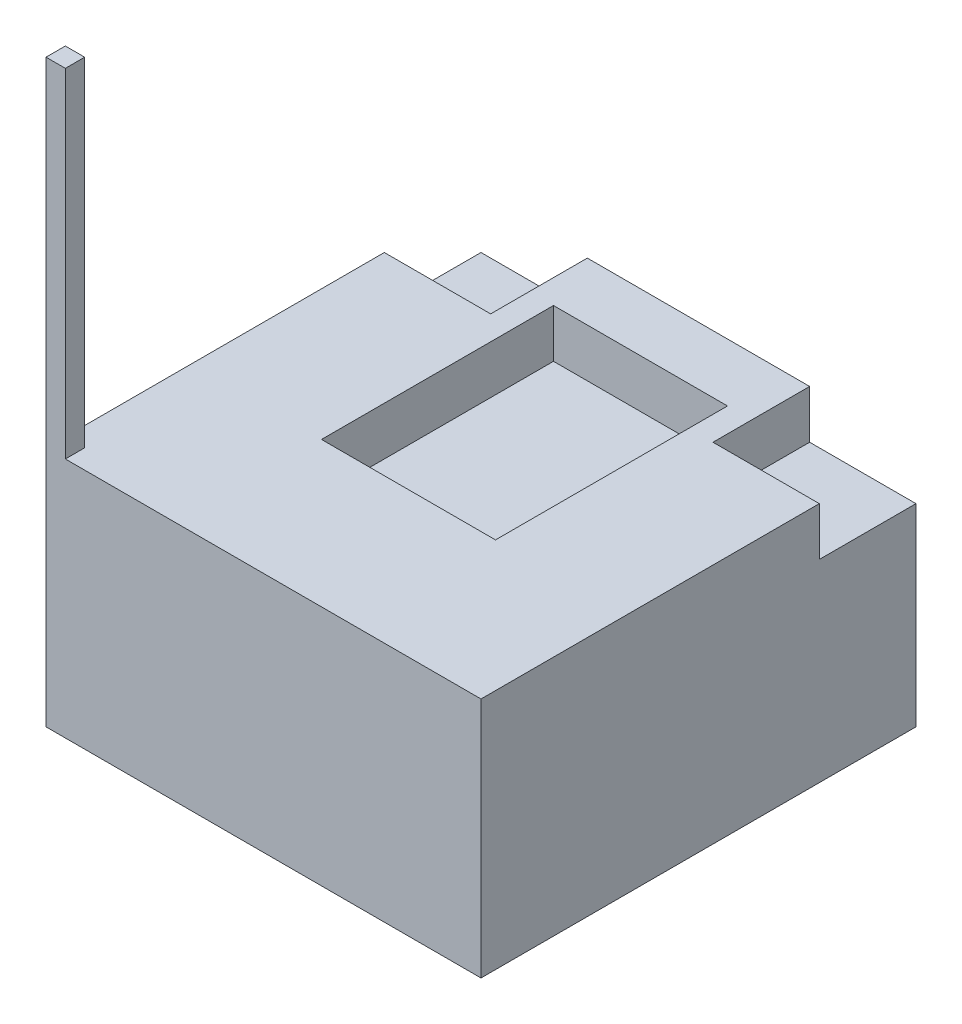
SolidWorks part; units mm, degrees
ref_plane "前视基准面" through (0, 0, 0) normal (0, 0, 1) x (1, 0, 0)
ref_plane "上视基准面" through (0, 0, 0) normal (0, 1, 0) x (1, 0, 0)
ref_plane "右视基准面" through (0, 0, 0) normal (1, 0, 0) x (0, 0, -1)
sketch "草图1" plane through (0, 0, 0) normal (0, 1, 0) x (1, 0, 0)
  line L1 (-225, 225) -> (225, 225)
  line L2 (-225, 225) -> (-225, -225)
  line L3 (-225, -225) -> (225, -225)
  line L4 (225, 225) -> (225, -225)
  line L5 (-225, 225) -> (225, -225) construction
  line L6 (-225, -225) -> (225, 225) construction
  point P0 (0, 0)
  dimension "D1" = 450
  dimension "D2" = 450
extrude "凸台-拉伸1" add sketch "草图1" along normal blind 250
sketch "草图2" plane through (0, 250, 0) normal (0, 1, 0) x (1, 0, 0)
  line L0 (0, 225) -> (0, 45) construction
  line L1 (-90, 165) -> (90, 165)
  line L2 (-90, 165) -> (-90, -75)
  line L3 (-90, -75) -> (90, -75)
  line L4 (90, 165) -> (90, -75)
  line L5 (-90, 165) -> (90, -75) construction
  line L6 (-90, -75) -> (90, 165) construction
  line L7 (225, 225) -> (-225, 225) construction
  point P0 (0, 45)
  dimension "D1" = 240
  dimension "D2" = 180
  dimension "D3" = 60
extrude "切除-拉伸1" cut sketch "草图2" against normal blind 50
sketch "草图3" plane through (0, 250, 0) normal (0, 1, 0) x (1, 0, 0)
  line L1 (-225, 225) -> (-115, 225)
  line L2 (-225, 225) -> (-225, 125)
  line L3 (-225, 125) -> (-115, 125)
  line L4 (-115, 225) -> (-115, 125)
  line L5 (225, 225) -> (115, 225)
  line L6 (225, 225) -> (225, 125)
  line L7 (225, 125) -> (115, 125)
  line L8 (115, 225) -> (115, 125)
  dimension "D1" = 110
  dimension "D2" = 100
extrude "切除-拉伸2" cut sketch "草图3" against normal blind 50
sketch "草图4" plane through (0, 0, -225) normal (0, 0, -1) x (-1, 0, 0)
  line L0 (0, 250) -> (0, 0) construction
  line L1 (-105, 242) -> (-97, 242)
  line L2 (-105, 242) -> (-105, 230)
  line L3 (-105, 230) -> (-97, 230)
  line L4 (-97, 242) -> (-97, 230)
  line L9 (-115, 250) -> (115, 250) construction
  line L10 (-225, 0) -> (225, 0) construction
  line L11 (97, 242) -> (97, 230)
  line L12 (105, 230) -> (97, 230)
  line L13 (105, 242) -> (105, 230)
  line L14 (105, 242) -> (97, 242)
  dimension "D1" = 8
  dimension "D2" = 12
  dimension "D3" = 105
  dimension "D4" = 230
extrude "切除-拉伸3" cut sketch "草图4" against normal blind 20
sketch "草图5" plane through (0, 0, -125) normal (0, 0, -1) x (-1, 0, 0)
  line L0 (105, 242) -> (97, 242) construction
  line L1 (212, 242) -> (220, 242)
  line L2 (212, 242) -> (212, 230)
  line L3 (212, 230) -> (220, 230)
  line L4 (220, 242) -> (220, 230)
  line L5 (97, 230) -> (105, 230) construction
  dimension "D1" = 8
  dimension "D2" = 220
extrude "切除-拉伸4" cut sketch "草图5" against normal blind 20
sketch "草图6" plane through (0, 0, 0) normal (0, -1, 0) x (1, 0, 0)
  line L1 (-225, 225) -> (-205, 225)
  line L2 (-225, 225) -> (-225, 205)
  line L3 (-225, 205) -> (-205, 205)
  line L4 (-205, 225) -> (-205, 205)
  dimension "D1" = 20
  dimension "D2" = 20
extrude "凸台-拉伸2" add sketch "草图6" against normal blind 600
sketch "草图7" plane through (0, 0, 225) normal (0, 0, 1) x (1, 0, 0)
  line L1 (-225, 0) -> (-205, 0)
  line L2 (-225, 0) -> (-225, 20)
  line L3 (-225, 20) -> (-205, 20)
  line L4 (-205, 0) -> (-205, 20)
  dimension "D1" = 20
extrude "凸台-拉伸3" add sketch "草图7" against normal blind 600
